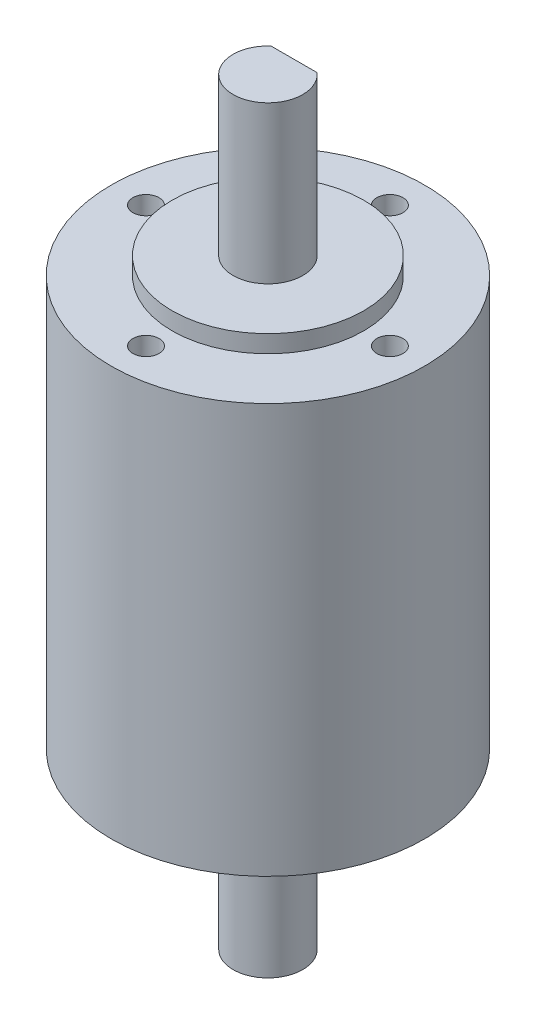
SolidWorks part; units mm, degrees
ref_plane "前视基准面" through (0, 0, 0) normal (0, 0, 1) x (1, 0, 0)
ref_plane "上视基准面" through (0, 0, 0) normal (0, 1, 0) x (1, 0, 0)
ref_plane "右视基准面" through (0, 0, 0) normal (1, 0, 0) x (0, 0, -1)
other "Configuration Table"
sketch "草图1" plane through (0, 0, 0) normal (0, 1, 0) x (1, 0, 0)
  circle A0 centre (0, 0) radius 18
  dimension "D1" = 36
extrude "凸台-拉伸1" add sketch "草图1" along normal blind 47
sketch "草图2" plane through (0, 47, 0) normal (0, 1, 0) x (1, 0, 0)
  circle A0 centre (0, 0) radius 11
  dimension "D1" = 22
extrude "凸台-拉伸2" add sketch "草图2" along normal blind 2
sketch "草图3" plane through (0, 0, 0) normal (0, -1, 0) x (1, 0, 0)
  circle A0 centre (0, 0) radius 11
  dimension "D1" = 22
extrude "凸台-拉伸3" add sketch "草图3" along normal blind 2
sketch "草图4" plane through (0, -2, 0) normal (0, -1, 0) x (1, 0, 0)
  circle A0 centre (0, 0) radius 4
  dimension "D1" = 8
extrude "凸台-拉伸4" add sketch "草图4" along normal blind 18
sketch "草图5" plane through (0, 49, 0) normal (0, 1, 0) x (1, 0, 0)
  circle A0 centre (0, 0) radius 4
  dimension "D1" = 8
extrude "凸台-拉伸5" add sketch "草图5" along normal blind 18
sketch "草图6" plane through (0, 67, 0) normal (0, 1, 0) x (1, 0, 0)
  line L1 (-4.794, 3) -> (4.4584, 3)
  line L2 (-4.794, 3) -> (-4.794, 7.6022)
  line L3 (-4.794, 7.6022) -> (4.4584, 7.6022)
  line L4 (4.4584, 3) -> (4.4584, 7.6022)
  dimension "D1" = 3
extrude "切除-拉伸1" cut sketch "草图6" against normal blind 15
sketch "草图7" plane through (0, -20, 0) normal (0, -1, 0) x (1, 0, 0)
  line L4 (4.4584, -3) -> (-4.794, -3)
  line L5 (4.4584, -7.6022) -> (4.4584, -3)
  line L6 (-4.794, -7.6022) -> (4.4584, -7.6022)
  line L7 (-4.794, -3) -> (-4.794, -7.6022)
  line L8 (4.4584, -3) -> (-4.794, -3)
  line L9 (4.4584, -7.6022) -> (4.4584, -3)
  line L10 (-4.794, -7.6022) -> (4.4584, -7.6022)
  line L11 (-4.794, -3) -> (-4.794, -7.6022)
  dimension "D1" = 0
extrude "切除-拉伸2" cut sketch "草图7" against normal blind 15
sketch "草图8" plane through (0, 0, 0) normal (0, -1, 0) x (1, 0, 0)
  line L0 (0, 0) -> (0, 14) construction
  circle A0 centre (0, 14) radius 1.5
  circle A1 centre (14, 0) radius 1.5
  circle A2 centre (0, -14) radius 1.5
  circle A3 centre (-14, 0) radius 1.5
  point P4 (-16.9708, -0.5753)
  point P5 (0, 0)
  point P13 (0, 0)
  dimension "D1" = 3
  dimension "D2" = 14
  dimension "D3" = 4
extrude "切除-拉伸3" cut sketch "草图8" against normal blind 6
sketch "草图9" plane through (0, 47, 0) normal (0, 1, 0) x (1, 0, 0)
  circle A1 centre (-14, 0) radius 1.5
  circle A2 centre (-14, 0) radius 1.5
  circle A3 centre (0, 14) radius 1.5
  circle A4 centre (0, 14) radius 1.5
  circle A5 centre (14, 0) radius 1.5
  circle A6 centre (14, 0) radius 1.5
  circle A7 centre (0, -14) radius 1.5
  circle A8 centre (0, -14) radius 1.5
  dimension "D1" = 0
  dimension "D2" = 0
  dimension "D3" = 0
  dimension "D4" = 0
extrude "切除-拉伸4" cut sketch "草图9" against normal blind 6
